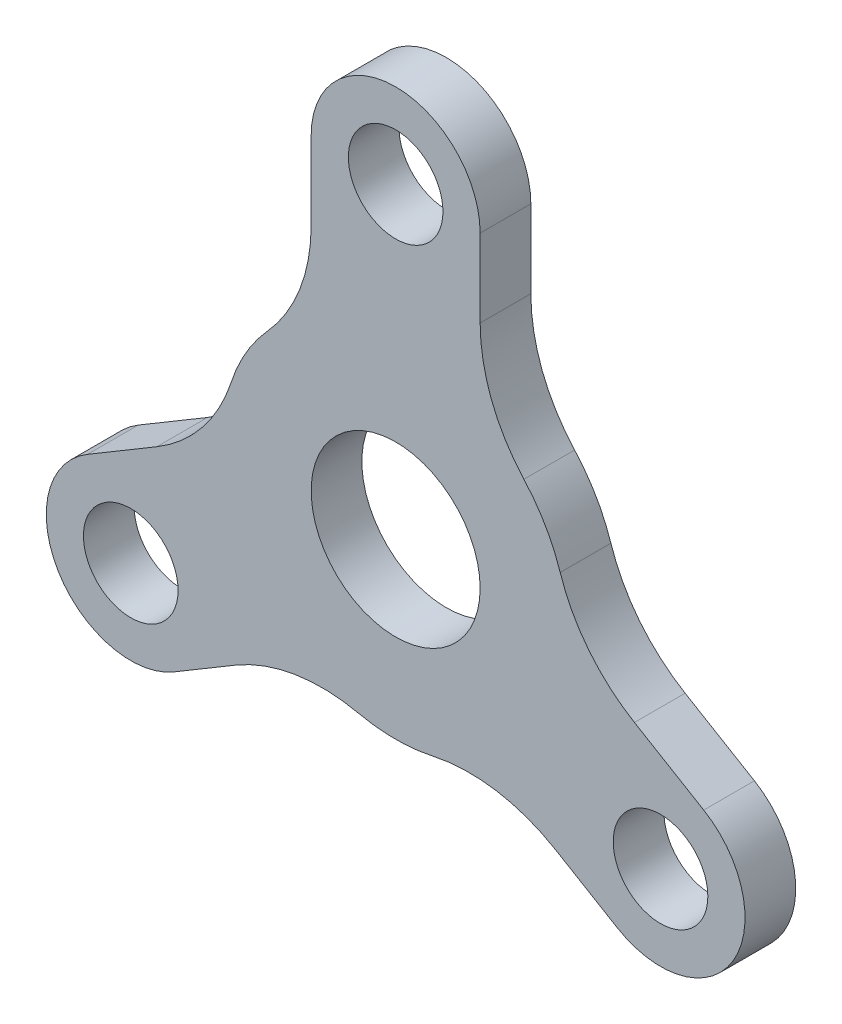
SolidWorks part; units mm, degrees
ref_plane "Alzado" through (0, 0, 0) normal (0, 0, 1) x (1, 0, 0)
ref_plane "Planta" through (0, 0, 0) normal (0, 1, 0) x (1, 0, 0)
ref_plane "Vista lateral" through (0, 0, 0) normal (1, 0, 0) x (0, 0, -1)
sketch "Croquis1" plane through (0, 0, 0) normal (0, 0, 1) x (1, 0, 0)
  line L0 (-18.2318, -4.7531) -> (-10.2435, 0)
  line L1 (-13.1183, -13.3469) -> (-5.359, -8.7299)
  line L2 (13.1183, -13.3469) -> (5.359, -8.7299)
  line L3 (-13.1183, -13.3469) -> (-18.2318, -4.7531)
  line L7 (13.1183, -13.3469) -> (18.2318, -4.7531)
  line L11 (-5, 18.2) -> (5, 18.2)
  line L15 (18.2318, -4.7531) -> (10.2435, 0)
  line L16 (-5, 18.2) -> (-5, 8.9404)
  line L17 (5, 18.2) -> (5, 8.9404)
  circle A0 centre (0, 18.2) radius 5
  circle A1 centre (15.6751, -9.05) radius 5
  circle A2 centre (-15.6751, -9.05) radius 5
  circle A3 centre (0, 0) radius 10.2435
  dimension "D7" = 10
  dimension "D8" = 10
  dimension "D9" = 10
  dimension "D1" = 90
  dimension "D2" = 90
  dimension "D3" = 90
  dimension "D4" = 18.1
  dimension "D5" = 18.1
  dimension "D6" = 18.2
  dimension "D10" = 90
  dimension "D11" = 90
  dimension "D12" = 90
extrude "Saliente-Extruir1" add sketch "Croquis1" along normal blind 3 contours L3 A2 | L3 A2 | A3 L0 A2 L1 | A3 | A3 L2 A1 L15 | A3 L17 A0 L16 | L11 A0 | L11 A0
sketch "Croquis2" plane through (0, 0, 3) normal (0, 0, 1) x (1, 0, 0)
  circle A0 centre (0, 18.2) radius 2.8
  circle A1 centre (15.6751, -9.05) radius 2.8
  circle A2 centre (-15.6751, -9.05) radius 2.8
  dimension "D1" = 5.6
  dimension "D2" = 5.6
  dimension "D3" = 5.6
sketch "Croquis3" plane through (0, 0, 3) normal (0, 0, 1) x (1, 0, 0)
  circle A0 centre (0, 0) radius 5
  dimension "D1" = 10
extrude "Cortar-Extruir1" cut sketch "Croquis2" against normal blind 10
extrude "Cortar-Extruir2" cut sketch "Croquis3" against normal blind 10
fillet "Redondeo1" radius 10 6 edges at (-5.359, -8.7299, 1.5) (5.359, -8.7299, 1.5) (10.2435, 0, 1.5) (5, 8.9404, 1.5) (-5, 8.9404, 1.5) (-10.2435, 0, 1.5)
